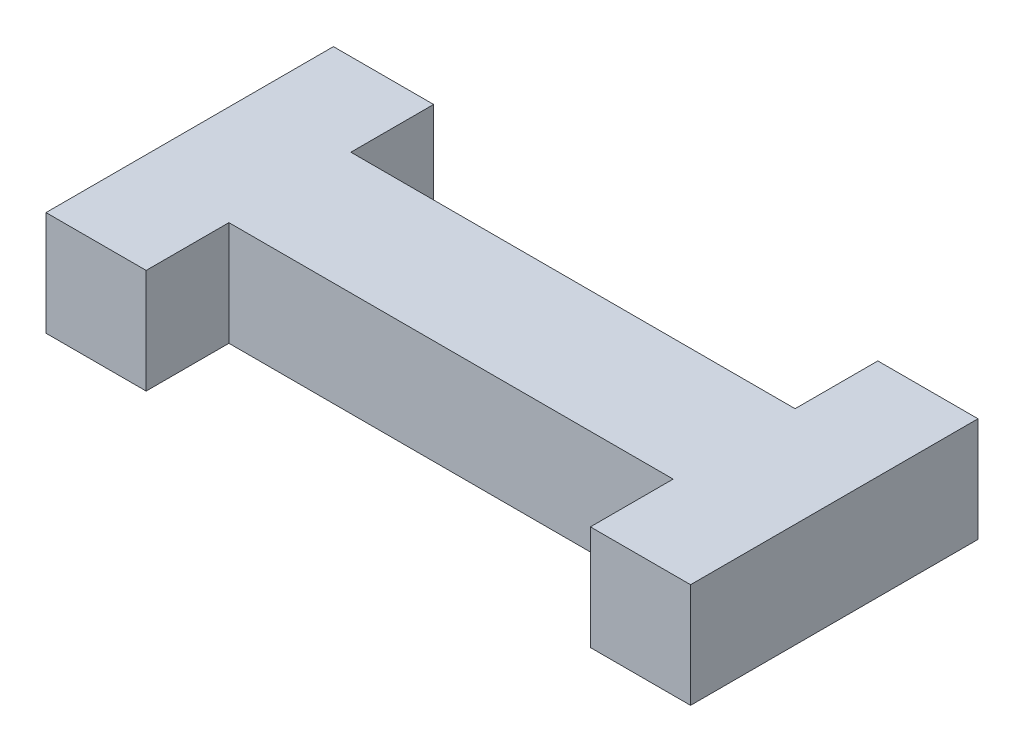
SolidWorks part; units mm, degrees
ref_plane "Front Plane" through (0, 0, 0) normal (0, 0, 1) x (1, 0, 0)
ref_plane "Top Plane" through (0, 0, 0) normal (0, 1, 0) x (1, 0, 0)
ref_plane "Right Plane" through (0, 0, 0) normal (1, 0, 0) x (0, 0, -1)
sketch "Sketch1" plane through (0, 0, 0) normal (0, 1, 0) x (1, 0, 0)
  line L0 (0, 0) -> (0, 22.3516) construction
  line L1 (0, 0) -> (-41.4702, 0) construction
  line L2 (12.954, 3.556) -> (-12.954, 3.556)
  line L3 (-12.954, 3.556) -> (-12.954, 8.382)
  line L4 (-12.954, 8.382) -> (-18.796, 8.382)
  line L5 (-18.796, 8.382) -> (-18.796, -8.382)
  line L6 (12.954, 3.556) -> (12.954, 8.382)
  line L7 (18.796, 8.382) -> (18.796, -8.382)
  line L8 (12.954, 8.382) -> (18.796, 8.382)
  line L9 (12.954, -3.556) -> (12.954, -8.382)
  line L10 (12.954, -8.382) -> (18.796, -8.382)
  line L11 (12.954, -3.556) -> (-12.954, -3.556)
  line L12 (-12.954, -3.556) -> (-12.954, -8.382)
  line L13 (-12.954, -8.382) -> (-18.796, -8.382)
  point P6 (-25.0242, 0)
  point P11 (0, 3.556)
  point P17 (18.796, 0)
  point P20 (-18.796, 0)
  dimension "D1" = 12.954
  dimension "D2" = 5.842
  dimension "D3" = 4.826
  dimension "D4" = 3.556
extrude "Boss-Extrude1" add sketch "Sketch1" along normal blind 6.096
